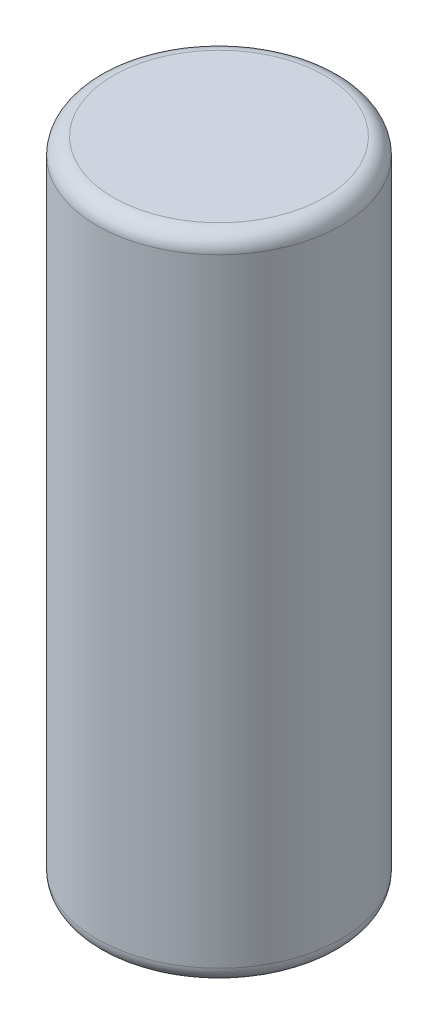
SolidWorks part; units mm, degrees
material "Plain Carbon Steel"
ref_plane "Front Plane" through (0, 0, 0) normal (0, 0, 1) x (1, 0, 0)
ref_plane "Top Plane" through (0, 0, 0) normal (0, 1, 0) x (1, 0, 0)
ref_plane "Right Plane" through (0, 0, 0) normal (1, 0, 0) x (0, 0, -1)
sketch "Sketch1" plane through (0, 0, 0) normal (0, 1, 0) x (1, 0, 0)
  line L2 (0, -55) -> (0, 55) construction
  circle A1 centre (0, 0) radius 75
  point P3 (0, 0)
  point P6 (0, 0)
  dimension "D1" = 150
extrude "Boss-Extrude1" add sketch "Sketch1" along normal mid plane 400
fillet "Fillet1" radius 10 2 edges at (0, 200, 75) (0, -200, 75)
